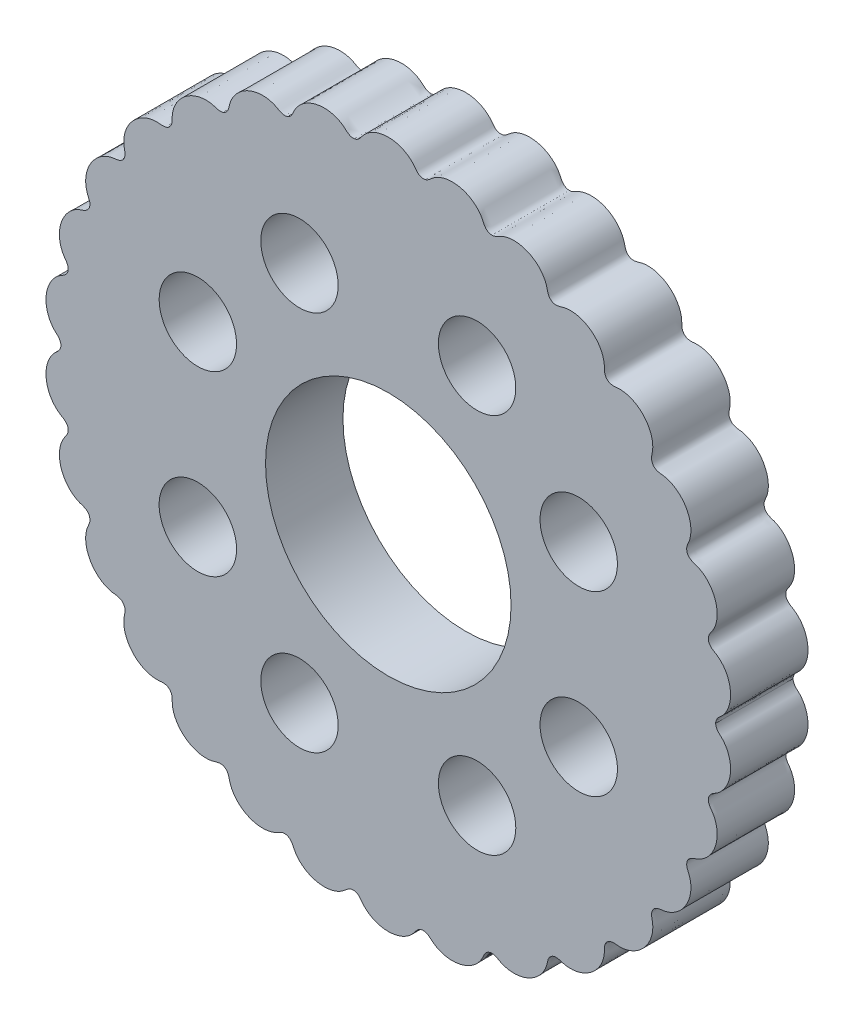
SolidWorks part; units mm, degrees
ref_plane "Plan de face" through (0, 0, 0) normal (0, 0, 1) x (1, 0, 0)
ref_plane "Plan de dessus" through (0, 0, 0) normal (0, 1, 0) x (1, 0, 0)
ref_plane "Plan de droite" through (0, 0, 0) normal (1, 0, 0) x (0, 0, -1)
sketch "Esquisse1" plane through (0, 0, 0) normal (0, 0, 1) x (1, 0, 0)
  line L0 (-1000, 0) -> (49000, 0) construction
  spline S0 degree 4 poles (29.8631, 8.2305) (29.8499, 8.1217) (29.8133, 7.9053) (29.7416, 7.64) (29.6157, 7.3353) (29.4839, 7.095) (29.3642, 6.911) (29.2467, 6.7537) (29.1538, 6.6056) (29.0902, 6.432) (29.0737, 6.2397) (29.1354, 6.023) (29.2904, 5.838) (29.4774, 5.7198) (29.6579, 5.6163) (29.8231, 5.5082) (30.0196, 5.3594) (30.2372, 5.1583) (30.5232, 4.8242) (30.8216, 4.3213) (31.0469, 3.679) (31.1337, 2.9091) (31.0567, 2.2277) (30.8902, 1.7108) (30.7109, 1.353) (30.5728, 1.1334) (30.4496, 0.9663) (30.3139, 0.8094) (30.1671, 0.6626) (30.0393, 0.549) (29.9425, 0.4546) (29.8803, 0.3777) (29.8449, 0.3262) (29.8141, 0.2716) (29.7888, 0.2141) (29.7717, 0.1632) (29.761, 0.1169) (29.7536, 0.0672) (29.7495, 0.017) (29.7494, -0.0206) (29.7556, -0.0898) (29.7678, -0.1499) (29.7904, -0.2203) (29.8284, -0.303) (29.8828, -0.3847) (29.9529, -0.4642) (30.04, -0.5488) (30.1416, -0.6407) (30.2572, -0.7512) (30.3813, -0.8854) (30.4962, -1.0277) (30.6276, -1.2147) (30.7721, -1.4641) (30.9126, -1.7829) (31.0276, -2.1744) (31.0935, -2.591) (31.107, -3.0187) (31.0662, -3.4508) (30.9693, -3.8803) (30.8145, -4.2991) (30.6117, -4.6792) (30.3965, -4.9766) (30.1917, -5.1998) (30.0146, -5.3603) (29.8643, -5.4786) (29.7061, -5.5858) (29.542, -5.684) (29.3671, -5.785) (29.2042, -5.9269) (29.0936, -6.1295) (29.0703, -6.371) (29.1391, -6.5914) (29.2598, -6.7697) (29.3791, -6.934) (29.4834, -7.0955) (29.5997, -7.3056) (29.715, -7.5703) (29.8147, -7.8969) (29.8798, -8.2857) (29.896, -8.684) (29.8631, -9.0858) (29.7829, -9.4799) (29.6574, -9.8612) (29.4885, -10.2243) (29.2783, -10.5643) (29.0303, -10.8742) (28.7824, -11.1148) (28.5506, -11.2952) (28.3468, -11.4258) (28.1768, -11.5188) (28.0006, -11.599) (27.8193, -11.6676) (27.6244, -11.7296) (27.4217, -11.8089) (27.242, -11.9571) (27.1301, -12.1734) (27.113, -12.404) (27.1707, -12.6114) (27.2542, -12.795) (27.3276, -12.9715) (27.3906, -13.1518) (27.4404, -13.3363) (27.4866, -13.5706) (27.5177, -13.8717) (27.5133, -14.2384) (27.4499, -14.6642) (27.3252, -15.0926) (27.1465, -15.4978) (26.919, -15.8739) (26.6474, -16.2153) (26.3365, -16.5168) (26.0024, -16.764) (25.654, -16.9563) (25.3418, -17.0779) (25.0791, -17.148) (24.8562, -17.1866) (24.6765, -17.2082) (24.4854, -17.2287) (24.2872, -17.2853) (24.1038, -17.4139) (23.9758, -17.6159) (23.9376, -17.8434) (23.9703, -18.0586) (24.0141, -18.2584) (24.0453, -18.4498) (24.0639, -18.6424) (24.0684, -18.8361) (24.0572, -19.0779) (24.0169, -19.3689) (23.9324, -19.7039) (23.7881, -20.0736) (23.5988, -20.4256) (23.3687, -20.7534) (23.1013, -21.0528) (22.8001, -21.3193) (22.4685, -21.5487) (22.1155, -21.7338) (21.7463, -21.8718) (21.4135, -21.9488) (21.1267, -21.9813) (20.8866, -21.9856) (20.6945, -21.9761) (20.4927, -21.9549) (20.2778, -21.9395) (20.0526, -21.9901) (19.8551, -22.131) (19.7349, -22.3281) (19.6935, -22.5401) (19.6935, -22.7421) (19.6905, -22.9333) (19.6768, -23.124) (19.6495, -23.3133) (19.599, -23.5469) (19.5081, -23.8358) (19.3582, -24.1709) (19.1304, -24.5365) (18.8451, -24.88) (18.5216, -25.1787) (18.1677, -25.4301) (17.7906, -25.6322) (17.3968, -25.7835) (17.0003, -25.8796) (16.6085, -25.9224) (16.2742, -25.9148) (16.002, -25.8785) (15.7793, -25.8278) (15.6036, -25.7769) (15.4169, -25.7147) (15.2087, -25.6689) (14.9779, -25.6954) (14.7639, -25.8189) (14.6256, -26.0056) (14.5611, -26.2088) (14.5217, -26.4015) (14.4779, -26.5791) (14.4104, -26.7974) (14.3058, -27.0513) (14.1452, -27.3445) (13.9122, -27.6625) (13.6308, -27.9579) (13.3029, -28.2232) (12.9393, -28.4488) (12.5446, -28.6295) (12.1242, -28.7604) (11.6841, -28.8357) (11.2535, -28.8501) (10.8884, -28.8124) (10.5927, -28.7466) (10.3651, -28.6736) (10.1875, -28.6026) (10.0156, -28.5191) (9.8485, -28.4261) (9.6736, -28.3252) (9.4693, -28.255) (9.2385, -28.2605) (9.0177, -28.3611) (8.8612, -28.5309) (8.7671, -28.7246) (8.6846, -28.91) (8.5968, -29.0812) (8.473, -29.2869) (8.3014, -29.519) (8.0684, -29.7687) (7.7643, -30.0195) (7.4274, -30.2327) (7.0631, -30.4051) (6.6816, -30.5327) (6.2887, -30.6146) (5.8897, -30.6499) (5.4902, -30.6379) (5.0979, -30.5781) (4.7655, -30.4837) (4.4934, -30.3731) (4.2784, -30.2619) (4.1128, -30.1612) (3.9553, -30.0487) (3.8052, -29.926) (3.6541, -29.7882) (3.484, -29.6523) (3.2679, -29.5716) (3.029, -29.5815) (2.8259, -29.676) (2.6778, -29.8193) (2.5645, -29.9746) (2.456, -30.1194) (2.311, -30.2931) (2.119, -30.4856) (1.8576, -30.6952) (1.5168, -30.9007) (1.1357, -31.0665) (0.7192, -31.185) (0.2877, -31.2495) (-0.1517, -31.2585) (-0.592, -31.2106) (-1.0254, -31.1045) (-1.4258, -30.9464) (-1.7456, -30.7669) (-1.9908, -30.5894) (-2.1706, -30.4322) (-2.3055, -30.2968) (-2.4301, -30.1521) (-2.5463, -30.0003) (-2.6635, -29.8363) (-2.8143, -29.6826) (-3.0226, -29.582) (-3.2659, -29.5708) (-3.484, -29.6523) (-3.654, -29.7882) (-3.8052, -29.926) (-3.9553, -30.0487) (-4.1128, -30.1612) (-4.2784, -30.2619) (-4.4934, -30.3731) (-4.7655, -30.4837) (-5.0979, -30.5781) (-5.4902, -30.6379) (-5.8897, -30.6499) (-6.2887, -30.6146) (-6.6816, -30.5327) (-7.0631, -30.4051) (-7.4274, -30.2327) (-7.7643, -30.0195) (-8.0684, -29.7687) (-8.3014, -29.519) (-8.473, -29.2869) (-8.5968, -29.0812) (-8.6846, -28.91) (-8.7671, -28.7246) (-8.8612, -28.5309) (-9.0177, -28.3611) (-9.2385, -28.2605) (-9.4693, -28.255) (-9.6736, -28.3252) (-9.8485, -28.4261) (-10.0156, -28.5191) (-10.1875, -28.6026) (-10.3651, -28.6736) (-10.5927, -28.7466) (-10.8884, -28.8124) (-11.2535, -28.8501) (-11.6841, -28.8357) (-12.1242, -28.7604) (-12.5446, -28.6295) (-12.9393, -28.4488) (-13.3029, -28.2232) (-13.6308, -27.9579) (-13.9122, -27.6625) (-14.1452, -27.3445) (-14.3058, -27.0513) (-14.4104, -26.7974) (-14.4779, -26.5791) (-14.5217, -26.4015) (-14.5611, -26.2088) (-14.6256, -26.0056) (-14.7639, -25.8189) (-14.9779, -25.6954) (-15.2087, -25.6689) (-15.4169, -25.7147) (-15.6036, -25.7769) (-15.7793, -25.8278) (-16.002, -25.8785) (-16.2742, -25.9148) (-16.6085, -25.9224) (-17.0003, -25.8796) (-17.3968, -25.7835) (-17.7906, -25.6322) (-18.1677, -25.4301) (-18.5216, -25.1787) (-18.8451, -24.88) (-19.1304, -24.5365) (-19.3582, -24.1709) (-19.5081, -23.8358) (-19.599, -23.5469) (-19.6495, -23.3133) (-19.6768, -23.124) (-19.6905, -22.9333) (-19.6935, -22.7421) (-19.6935, -22.5401) (-19.7349, -22.3281) (-19.8551, -22.131) (-20.0526, -21.9901) (-20.2778, -21.9395) (-20.4927, -21.9549) (-20.6945, -21.9761) (-20.8866, -21.9856) (-21.1267, -21.9813) (-21.4135, -21.9488) (-21.7463, -21.8718) (-22.1155, -21.7338) (-22.4685, -21.5487) (-22.8001, -21.3193) (-23.1013, -21.0528) (-23.3687, -20.7534) (-23.5988, -20.4256) (-23.7881, -20.0736) (-23.9324, -19.7039) (-24.0169, -19.3689) (-24.0572, -19.0779) (-24.0684, -18.8361) (-24.0639, -18.6424) (-24.0453, -18.4498) (-24.0141, -18.2584) (-23.9703, -18.0586) (-23.9376, -17.8434) (-23.9758, -17.6159) (-24.1038, -17.4139) (-24.2872, -17.2853) (-24.4854, -17.2287) (-24.6765, -17.2082) (-24.8562, -17.1866) (-25.0791, -17.148) (-25.3418, -17.0779) (-25.654, -16.9563) (-26.0024, -16.764) (-26.3365, -16.5168) (-26.6474, -16.2153) (-26.919, -15.8739) (-27.1465, -15.4978) (-27.3252, -15.0926) (-27.4499, -14.6642) (-27.5133, -14.2384) (-27.5177, -13.8717) (-27.4866, -13.5706) (-27.4404, -13.3363) (-27.3906, -13.1518) (-27.3276, -12.9715) (-27.2542, -12.795) (-27.1707, -12.6114) (-27.113, -12.404) (-27.1301, -12.1734) (-27.242, -11.9571) (-27.4217, -11.8089) (-27.6244, -11.7296) (-27.8193, -11.6676) (-28.0006, -11.599) (-28.1768, -11.5188) (-28.3468, -11.4258) (-28.5506, -11.2952) (-28.7824, -11.1148) (-29.0303, -10.8742) (-29.2783, -10.5643) (-29.4885, -10.2243) (-29.6574, -9.8612) (-29.7829, -9.4799) (-29.8631, -9.0858) (-29.896, -8.684) (-29.8798, -8.2857) (-29.8147, -7.8969) (-29.715, -7.5703) (-29.5997, -7.3056) (-29.4834, -7.0955) (-29.3791, -6.934) (-29.2598, -6.7697) (-29.1391, -6.5914) (-29.0703, -6.371) (-29.0936, -6.1295) (-29.2042, -5.9269) (-29.3671, -5.785) (-29.542, -5.684) (-29.7061, -5.5858) (-29.8643, -5.4786) (-30.0146, -5.3603) (-30.1917, -5.1998) (-30.3965, -4.9766) (-30.6117, -4.6792) (-30.8145, -4.2991) (-30.9693, -3.8803) (-31.0662, -3.4508) (-31.107, -3.0187) (-31.0935, -2.591) (-31.0276, -2.1744) (-30.9126, -1.7829) (-30.7537, -1.4222) (-30.58, -1.1364) (-30.4124, -0.919) (-30.2572, -0.7512) (-30.1416, -0.6407) (-30.04, -0.5488) (-29.9529, -0.4642) (-29.8828, -0.3847) (-29.8284, -0.303) (-29.7904, -0.2203) (-29.7678, -0.1499) (-29.7556, -0.0898) (-29.7494, -0.0206) (-29.7495, 0.0226) (-29.7561, 0.094) (-29.7693, 0.1557) (-29.7888, 0.2141) (-29.8141, 0.2716) (-29.8449, 0.3262) (-29.8803, 0.3778) (-29.9262, 0.4344) (-29.9834, 0.4947) (-30.0703, 0.5765) (-30.1854, 0.6811) (-30.3139, 0.8093) (-30.4835, 1.0056) (-30.6621, 1.2611) (-30.8291, 1.576) (-30.9678, 1.9517) (-31.0574, 2.3341) (-31.1011, 2.7166) (-31.1012, 3.1978) (-31.0148, 3.7704) (-30.8216, 4.3213) (-30.5232, 4.8242) (-30.2372, 5.1583) (-30.0196, 5.3594) (-29.8231, 5.5082) (-29.6579, 5.6163) (-29.4774, 5.7198) (-29.2904, 5.838) (-29.1354, 6.023) (-29.0737, 6.2397) (-29.0902, 6.432) (-29.1538, 6.6056) (-29.2467, 6.7537) (-29.3642, 6.911) (-29.4839, 7.095) (-29.6157, 7.3353) (-29.7416, 7.64) (-29.8133, 7.9053) (-29.8499, 8.1217) (-29.8631, 8.2305) knots 0 0 0 0 0 0.003392 0.006784 0.00848 0.010176 0.011872 0.013568 0.014566 0.015563 0.017559 0.01944 0.02132 0.022846 0.024371 0.025896 0.027421 0.030471 0.033522 0.039468 0.045414 0.051361 0.057307 0.060517 0.062121 0.063726 0.065331 0.066935 0.06854 0.070145 0.070628 0.071112 0.071596 0.07208 0.072564 0.073048 0.073289 0.073531 0.074015 0.07448 0.074945 0.07541 0.075875 0.076805 0.077735 0.078442 0.079149 0.080563 0.081977 0.083391 0.084805 0.086218 0.089046 0.092302 0.095557 0.098813 0.102069 0.105514 0.10896 0.112405 0.115851 0.118808 0.120287 0.121766 0.123244 0.124723 0.126202 0.12768 0.1295 0.131319 0.133154 0.134989 0.136475 0.137961 0.139448 0.140934 0.143906 0.146878 0.14999 0.153103 0.156215 0.159327 0.162414 0.1655 0.168586 0.171672 0.174668 0.176165 0.177663 0.179161 0.180659 0.182156 0.183654 0.185506 0.187357 0.189175 0.190994 0.192471 0.193949 0.195426 0.196904 0.198382 0.199859 0.202814 0.206257 0.2097 0.213143 0.216586 0.219928 0.22327 0.226613 0.229955 0.232755 0.235555 0.236955 0.238355 0.239755 0.241155 0.242909 0.244663 0.246515 0.248366 0.249864 0.251362 0.252859 0.254357 0.255855 0.257353 0.260348 0.263434 0.266521 0.269607 0.272693 0.275805 0.278918 0.28203 0.285143 0.288115 0.291087 0.292573 0.294059 0.295545 0.297031 0.298866 0.300701 0.302521 0.30434 0.305819 0.307297 0.308776 0.310255 0.311733 0.313212 0.31617 0.319615 0.323061 0.326506 0.329952 0.333207 0.336463 0.339719 0.342974 0.345802 0.34863 0.350043 0.351457 0.352871 0.354285 0.356145 0.358005 0.359865 0.361725 0.363139 0.364553 0.365967 0.367381 0.370208 0.373036 0.376292 0.379547 0.382803 0.386059 0.389504 0.39295 0.396395 0.399841 0.402798 0.404277 0.405755 0.407234 0.408713 0.410191 0.41167 0.41349 0.415309 0.417144 0.418979 0.420465 0.421951 0.423437 0.424923 0.427896 0.430868 0.43398 0.437092 0.440205 0.443317 0.446403 0.44949 0.452576 0.455662 0.458657 0.460155 0.461653 0.463151 0.464649 0.466146 0.467644 0.469495 0.471347 0.473101 0.474856 0.476256 0.477656 0.479056 0.480456 0.483256 0.486055 0.489398 0.49274 0.496082 0.499424 0.502867 0.50631 0.509753 0.513196 0.516151 0.517629 0.519106 0.520584 0.522061 0.523539 0.525016 0.526835 0.528653 0.530505 0.532356 0.533854 0.535351 0.536849 0.538347 0.539845 0.541343 0.544338 0.547424 0.55051 0.553597 0.556683 0.559795 0.562908 0.56602 0.569132 0.572104 0.575077 0.576563 0.578049 0.579535 0.581021 0.582856 0.584691 0.58651 0.58833 0.589809 0.591287 0.592766 0.594245 0.595723 0.597202 0.600159 0.603605 0.60705 0.610496 0.613941 0.617197 0.620453 0.623708 0.626964 0.629792 0.632619 0.634033 0.635447 0.636861 0.638275 0.640135 0.641995 0.643855 0.645715 0.647129 0.648543 0.649957 0.65137 0.654198 0.657026 0.660281 0.663537 0.666793 0.670048 0.673494 0.676939 0.680385 0.68383 0.686788 0.688267 0.689745 0.691224 0.692703 0.694181 0.69566 0.697479 0.699299 0.701134 0.702969 0.704455 0.705941 0.707427 0.708913 0.711885 0.714857 0.71797 0.721082 0.724195 0.727307 0.730393 0.733479 0.736566 0.739652 0.742647 0.744145 0.745643 0.747141 0.748638 0.750136 0.751634 0.753485 0.755337 0.757091 0.758845 0.760245 0.761645 0.763045 0.764445 0.767245 0.770045 0.773387 0.77673 0.780072 0.783414 0.786857 0.7903 0.793743 0.797186 0.800141 0.801618 0.803096 0.804574 0.806051 0.807529 0.809006 0.810825 0.812643 0.814494 0.816346 0.817844 0.819341 0.820839 0.822337 0.823835 0.825332 0.828328 0.831414 0.8345 0.837586 0.840673 0.843785 0.846897 0.85001 0.853122 0.856094 0.859066 0.860552 0.862039 0.863525 0.865011 0.866846 0.868681 0.8705 0.87232 0.873798 0.875277 0.876756 0.878234 0.879713 0.881192 0.884149 0.887595 0.89104 0.894486 0.897931 0.901187 0.904443 0.907698 0.910954 0.913782 0.916609 0.918023 0.919437 0.920851 0.921558 0.922265 0.923195 0.924125 0.92459 0.925055 0.92552 0.925985 0.926469 0.926952 0.927436 0.92792 0.928404 0.928888 0.929372 0.929855 0.930658 0.93146 0.933065 0.934669 0.936274 0.939483 0.942693 0.945666 0.948639 0.951612 0.954586 0.960532 0.966478 0.969529 0.972579 0.974104 0.975629 0.977154 0.97868 0.98056 0.982441 0.984437 0.985434 0.986432 0.988128 0.989824 0.99152 0.993216 0.996608 1 1 1 1 1 construction
  spline S1 degree 4 poles (29.75, 0) (29.75, -0.0128) (29.751, -0.0384) (29.7556, -0.0898) (29.7678, -0.1499) (29.7904, -0.2203) (29.8284, -0.303) (29.8828, -0.3847) (29.9529, -0.4642) (30.04, -0.5488) (30.1416, -0.6407) (30.2572, -0.7512) (30.3813, -0.8854) (30.4962, -1.0277) (30.6276, -1.2147) (30.7721, -1.4641) (30.9126, -1.7829) (31.0276, -2.1744) (31.0935, -2.591) (31.107, -3.0187) (31.0662, -3.4508) (30.9693, -3.8803) (30.8145, -4.2991) (30.6117, -4.6792) (30.3965, -4.9766) (30.1917, -5.1998) (30.0146, -5.3603) (29.8643, -5.4786) (29.7061, -5.5858) (29.542, -5.684) (29.3671, -5.785) (29.2042, -5.9269) (29.0936, -6.1295) (29.0703, -6.371) (29.1391, -6.5914) (29.2598, -6.7697) (29.3791, -6.934) (29.4834, -7.0955) (29.5997, -7.3056) (29.715, -7.5703) (29.8147, -7.8969) (29.8798, -8.2857) (29.896, -8.684) (29.8631, -9.0858) (29.7829, -9.4799) (29.6574, -9.8612) (29.4885, -10.2243) (29.2783, -10.5643) (29.0303, -10.8742) (28.7824, -11.1148) (28.5506, -11.2952) (28.3468, -11.4258) (28.1768, -11.5188) (28.0006, -11.599) (27.8193, -11.6676) (27.6244, -11.7296) (27.4217, -11.8089) (27.242, -11.9571) (27.1301, -12.1734) (27.113, -12.404) (27.1707, -12.6114) (27.2542, -12.795) (27.3276, -12.9715) (27.3906, -13.1518) (27.4404, -13.3363) (27.4866, -13.5706) (27.5177, -13.8717) (27.5133, -14.2384) (27.4499, -14.6642) (27.3252, -15.0926) (27.1465, -15.4978) (26.919, -15.8739) (26.6474, -16.2153) (26.3365, -16.5168) (26.0024, -16.764) (25.654, -16.9563) (25.3418, -17.0779) (25.0791, -17.148) (24.8562, -17.1866) (24.6765, -17.2082) (24.4854, -17.2287) (24.2872, -17.2853) (24.1038, -17.4139) (23.9758, -17.6159) (23.9376, -17.8434) (23.9703, -18.0586) (24.0141, -18.2584) (24.0453, -18.4498) (24.0639, -18.6424) (24.0684, -18.8361) (24.0572, -19.0779) (24.0169, -19.3689) (23.9324, -19.7039) (23.7881, -20.0736) (23.5988, -20.4256) (23.3687, -20.7534) (23.1013, -21.0528) (22.8001, -21.3193) (22.4685, -21.5487) (22.1155, -21.7338) (21.7463, -21.8718) (21.4135, -21.9488) (21.1267, -21.9813) (20.8866, -21.9856) (20.6945, -21.9761) (20.4927, -21.9549) (20.2778, -21.9395) (20.0526, -21.9901) (19.8551, -22.131) (19.7349, -22.3281) (19.6935, -22.5401) (19.6935, -22.7421) (19.6905, -22.9333) (19.6768, -23.124) (19.6495, -23.3133) (19.599, -23.5469) (19.5081, -23.8358) (19.3582, -24.1709) (19.1304, -24.5365) (18.8451, -24.88) (18.5216, -25.1787) (18.1677, -25.4301) (17.7906, -25.6322) (17.3968, -25.7835) (17.0003, -25.8796) (16.6085, -25.9224) (16.2742, -25.9148) (16.002, -25.8785) (15.7793, -25.8278) (15.6036, -25.7769) (15.4169, -25.7147) (15.2087, -25.6689) (14.9779, -25.6954) (14.7639, -25.8189) (14.6256, -26.0056) (14.5611, -26.2088) (14.5217, -26.4015) (14.4779, -26.5791) (14.4104, -26.7974) (14.3058, -27.0513) (14.1452, -27.3445) (13.9122, -27.6625) (13.6308, -27.9579) (13.3029, -28.2232) (12.9393, -28.4488) (12.5446, -28.6295) (12.1242, -28.7604) (11.6841, -28.8357) (11.2535, -28.8501) (10.8884, -28.8124) (10.5927, -28.7466) (10.3651, -28.6736) (10.1875, -28.6026) (10.0156, -28.5191) (9.8485, -28.4261) (9.6736, -28.3252) (9.4693, -28.255) (9.2385, -28.2605) (9.0177, -28.3611) (8.8612, -28.5309) (8.7671, -28.7246) (8.6846, -28.91) (8.5968, -29.0812) (8.473, -29.2869) (8.3014, -29.519) (8.0684, -29.7687) (7.7643, -30.0195) (7.4274, -30.2327) (7.0631, -30.4051) (6.6816, -30.5327) (6.2887, -30.6146) (5.8897, -30.6499) (5.4902, -30.6379) (5.0979, -30.5781) (4.7655, -30.4837) (4.4934, -30.3731) (4.2784, -30.2619) (4.1128, -30.1612) (3.9553, -30.0487) (3.8052, -29.926) (3.6541, -29.7882) (3.484, -29.6523) (3.2679, -29.5716) (3.029, -29.5815) (2.8259, -29.676) (2.6778, -29.8193) (2.5645, -29.9746) (2.456, -30.1194) (2.311, -30.2931) (2.119, -30.4856) (1.8576, -30.6952) (1.5168, -30.9007) (1.1357, -31.0665) (0.7192, -31.185) (0.2877, -31.2495) (-0.1517, -31.2585) (-0.592, -31.2106) (-1.0254, -31.1045) (-1.4258, -30.9464) (-1.7456, -30.7669) (-1.9908, -30.5894) (-2.1706, -30.4322) (-2.3055, -30.2968) (-2.4301, -30.1521) (-2.5463, -30.0003) (-2.6635, -29.8363) (-2.8143, -29.6826) (-3.0226, -29.582) (-3.2659, -29.5708) (-3.484, -29.6523) (-3.654, -29.7882) (-3.8052, -29.926) (-3.9553, -30.0487) (-4.1128, -30.1612) (-4.2784, -30.2619) (-4.4934, -30.3731) (-4.7655, -30.4837) (-5.0979, -30.5781) (-5.4902, -30.6379) (-5.8897, -30.6499) (-6.2887, -30.6146) (-6.6816, -30.5327) (-7.0631, -30.4051) (-7.4274, -30.2327) (-7.7643, -30.0195) (-8.0684, -29.7687) (-8.3014, -29.519) (-8.473, -29.2869) (-8.5968, -29.0812) (-8.6846, -28.91) (-8.7671, -28.7246) (-8.8612, -28.5309) (-9.0177, -28.3611) (-9.2385, -28.2605) (-9.4693, -28.255) (-9.6736, -28.3252) (-9.8485, -28.4261) (-10.0156, -28.5191) (-10.1875, -28.6026) (-10.3651, -28.6736) (-10.5927, -28.7466) (-10.8884, -28.8124) (-11.2535, -28.8501) (-11.6841, -28.8357) (-12.1242, -28.7604) (-12.5446, -28.6295) (-12.9393, -28.4488) (-13.3029, -28.2232) (-13.6308, -27.9579) (-13.9122, -27.6625) (-14.1452, -27.3445) (-14.3058, -27.0513) (-14.4104, -26.7974) (-14.4779, -26.5791) (-14.5217, -26.4015) (-14.5611, -26.2088) (-14.6256, -26.0056) (-14.7639, -25.8189) (-14.9779, -25.6954) (-15.2087, -25.6689) (-15.4169, -25.7147) (-15.6036, -25.7769) (-15.7793, -25.8278) (-16.002, -25.8785) (-16.2742, -25.9148) (-16.6085, -25.9224) (-17.0003, -25.8796) (-17.3968, -25.7835) (-17.7906, -25.6322) (-18.1677, -25.4301) (-18.5216, -25.1787) (-18.8451, -24.88) (-19.1304, -24.5365) (-19.3582, -24.1709) (-19.5081, -23.8358) (-19.599, -23.5469) (-19.6495, -23.3133) (-19.6768, -23.124) (-19.6905, -22.9333) (-19.6935, -22.7421) (-19.6935, -22.5401) (-19.7349, -22.3281) (-19.8551, -22.131) (-20.0526, -21.9901) (-20.2778, -21.9395) (-20.4927, -21.9549) (-20.6945, -21.9761) (-20.8866, -21.9856) (-21.1267, -21.9813) (-21.4135, -21.9488) (-21.7463, -21.8718) (-22.1155, -21.7338) (-22.4685, -21.5487) (-22.8001, -21.3193) (-23.1013, -21.0528) (-23.3687, -20.7534) (-23.5988, -20.4256) (-23.7881, -20.0736) (-23.9324, -19.7039) (-24.0169, -19.3689) (-24.0572, -19.0779) (-24.0684, -18.8361) (-24.0639, -18.6424) (-24.0453, -18.4498) (-24.0141, -18.2584) (-23.9703, -18.0586) (-23.9376, -17.8434) (-23.9758, -17.6159) (-24.1038, -17.4139) (-24.2872, -17.2853) (-24.4854, -17.2287) (-24.6765, -17.2082) (-24.8562, -17.1866) (-25.0791, -17.148) (-25.3418, -17.0779) (-25.654, -16.9563) (-26.0024, -16.764) (-26.3365, -16.5168) (-26.6474, -16.2153) (-26.919, -15.8739) (-27.1465, -15.4978) (-27.3252, -15.0926) (-27.4499, -14.6642) (-27.5133, -14.2384) (-27.5177, -13.8717) (-27.4866, -13.5706) (-27.4404, -13.3363) (-27.3906, -13.1518) (-27.3276, -12.9715) (-27.2542, -12.795) (-27.1707, -12.6114) (-27.113, -12.404) (-27.1301, -12.1734) (-27.242, -11.9571) (-27.4217, -11.8089) (-27.6244, -11.7296) (-27.8193, -11.6676) (-28.0006, -11.599) (-28.1768, -11.5188) (-28.3468, -11.4258) (-28.5506, -11.2952) (-28.7824, -11.1148) (-29.0303, -10.8742) (-29.2783, -10.5643) (-29.4885, -10.2243) (-29.6574, -9.8612) (-29.7829, -9.4799) (-29.8631, -9.0858) (-29.896, -8.684) (-29.8798, -8.2857) (-29.8147, -7.8969) (-29.715, -7.5703) (-29.5997, -7.3056) (-29.4834, -7.0955) (-29.3791, -6.934) (-29.2598, -6.7697) (-29.1391, -6.5914) (-29.0703, -6.371) (-29.0936, -6.1295) (-29.2042, -5.9269) (-29.3671, -5.785) (-29.542, -5.684) (-29.7061, -5.5858) (-29.8643, -5.4786) (-30.0146, -5.3603) (-30.1917, -5.1998) (-30.3965, -4.9766) (-30.6117, -4.6792) (-30.8145, -4.2991) (-30.9693, -3.8803) (-31.0662, -3.4508) (-31.107, -3.0187) (-31.0935, -2.591) (-31.0276, -2.1744) (-30.9126, -1.7829) (-30.7537, -1.4222) (-30.58, -1.1364) (-30.4124, -0.919) (-30.2572, -0.7512) (-30.1416, -0.6407) (-30.04, -0.5488) (-29.9529, -0.4642) (-29.8828, -0.3847) (-29.8284, -0.303) (-29.7904, -0.2203) (-29.7678, -0.1499) (-29.7556, -0.0898) (-29.751, -0.0384) (-29.75, -0.0128) (-29.75, 0) knots 0.074015 0.074015 0.074015 0.074015 0.074015 0.07448 0.074945 0.07541 0.075875 0.076805 0.077735 0.078442 0.079149 0.080563 0.081977 0.083391 0.084805 0.086218 0.089046 0.092302 0.095557 0.098813 0.102069 0.105514 0.10896 0.112405 0.115851 0.118808 0.120287 0.121766 0.123244 0.124723 0.126202 0.12768 0.1295 0.131319 0.133154 0.134989 0.136475 0.137961 0.139448 0.140934 0.143906 0.146878 0.14999 0.153103 0.156215 0.159327 0.162414 0.1655 0.168586 0.171672 0.174668 0.176165 0.177663 0.179161 0.180659 0.182156 0.183654 0.185506 0.187357 0.189175 0.190994 0.192471 0.193949 0.195426 0.196904 0.198382 0.199859 0.202814 0.206257 0.2097 0.213143 0.216586 0.219928 0.22327 0.226613 0.229955 0.232755 0.235555 0.236955 0.238355 0.239755 0.241155 0.242909 0.244663 0.246515 0.248366 0.249864 0.251362 0.252859 0.254357 0.255855 0.257353 0.260348 0.263434 0.266521 0.269607 0.272693 0.275805 0.278918 0.28203 0.285143 0.288115 0.291087 0.292573 0.294059 0.295545 0.297031 0.298866 0.300701 0.302521 0.30434 0.305819 0.307297 0.308776 0.310255 0.311733 0.313212 0.31617 0.319615 0.323061 0.326506 0.329952 0.333207 0.336463 0.339719 0.342974 0.345802 0.34863 0.350043 0.351457 0.352871 0.354285 0.356145 0.358005 0.359865 0.361725 0.363139 0.364553 0.365967 0.367381 0.370208 0.373036 0.376292 0.379547 0.382803 0.386059 0.389504 0.39295 0.396395 0.399841 0.402798 0.404277 0.405755 0.407234 0.408713 0.410191 0.41167 0.41349 0.415309 0.417144 0.418979 0.420465 0.421951 0.423437 0.424923 0.427896 0.430868 0.43398 0.437092 0.440205 0.443317 0.446403 0.44949 0.452576 0.455662 0.458657 0.460155 0.461653 0.463151 0.464649 0.466146 0.467644 0.469495 0.471347 0.473101 0.474856 0.476256 0.477656 0.479056 0.480456 0.483256 0.486055 0.489398 0.49274 0.496082 0.499424 0.502867 0.50631 0.509753 0.513196 0.516151 0.517629 0.519106 0.520584 0.522061 0.523539 0.525016 0.526835 0.528653 0.530505 0.532356 0.533854 0.535351 0.536849 0.538347 0.539845 0.541343 0.544338 0.547424 0.55051 0.553597 0.556683 0.559795 0.562908 0.56602 0.569132 0.572104 0.575077 0.576563 0.578049 0.579535 0.581021 0.582856 0.584691 0.58651 0.58833 0.589809 0.591287 0.592766 0.594245 0.595723 0.597202 0.600159 0.603605 0.60705 0.610496 0.613941 0.617197 0.620453 0.623708 0.626964 0.629792 0.632619 0.634033 0.635447 0.636861 0.638275 0.640135 0.641995 0.643855 0.645715 0.647129 0.648543 0.649957 0.65137 0.654198 0.657026 0.660281 0.663537 0.666793 0.670048 0.673494 0.676939 0.680385 0.68383 0.686788 0.688267 0.689745 0.691224 0.692703 0.694181 0.69566 0.697479 0.699299 0.701134 0.702969 0.704455 0.705941 0.707427 0.708913 0.711885 0.714857 0.71797 0.721082 0.724195 0.727307 0.730393 0.733479 0.736566 0.739652 0.742647 0.744145 0.745643 0.747141 0.748638 0.750136 0.751634 0.753485 0.755337 0.757091 0.758845 0.760245 0.761645 0.763045 0.764445 0.767245 0.770045 0.773387 0.77673 0.780072 0.783414 0.786857 0.7903 0.793743 0.797186 0.800141 0.801618 0.803096 0.804574 0.806051 0.807529 0.809006 0.810825 0.812643 0.814494 0.816346 0.817844 0.819341 0.820839 0.822337 0.823835 0.825332 0.828328 0.831414 0.8345 0.837586 0.840673 0.843785 0.846897 0.85001 0.853122 0.856094 0.859066 0.860552 0.862039 0.863525 0.865011 0.866846 0.868681 0.8705 0.87232 0.873798 0.875277 0.876756 0.878234 0.879713 0.881192 0.884149 0.887595 0.89104 0.894486 0.897931 0.901187 0.904443 0.907698 0.910954 0.913782 0.916609 0.918023 0.919437 0.920851 0.921558 0.922265 0.923195 0.924125 0.92459 0.925055 0.92552 0.925985 0.925985 0.925985 0.925985 0.925985 construction
  spline S2 degree 4 poles (29.75, 0) (29.75, 0.0128) (29.751, 0.0384) (29.7556, 0.0898) (29.7678, 0.1499) (29.7904, 0.2203) (29.8284, 0.303) (29.8828, 0.3847) (29.9529, 0.4642) (30.04, 0.5488) (30.1416, 0.6407) (30.2572, 0.7512) (30.3813, 0.8854) (30.4962, 1.0277) (30.6276, 1.2147) (30.7721, 1.4641) (30.9126, 1.7829) (31.0276, 2.1744) (31.0935, 2.591) (31.107, 3.0187) (31.0662, 3.4508) (30.9693, 3.8803) (30.8145, 4.2991) (30.6117, 4.6792) (30.3965, 4.9766) (30.1917, 5.1998) (30.0146, 5.3603) (29.8643, 5.4786) (29.7061, 5.5858) (29.542, 5.684) (29.3671, 5.785) (29.2042, 5.9269) (29.0936, 6.1295) (29.0703, 6.371) (29.1391, 6.5914) (29.2598, 6.7697) (29.3791, 6.934) (29.4834, 7.0955) (29.5997, 7.3056) (29.715, 7.5703) (29.8147, 7.8969) (29.8798, 8.2857) (29.896, 8.684) (29.8631, 9.0858) (29.7829, 9.4799) (29.6574, 9.8612) (29.4885, 10.2243) (29.2783, 10.5643) (29.0303, 10.8742) (28.7824, 11.1148) (28.5506, 11.2952) (28.3468, 11.4258) (28.1768, 11.5188) (28.0006, 11.599) (27.8193, 11.6676) (27.6244, 11.7296) (27.4217, 11.8089) (27.242, 11.9571) (27.1301, 12.1734) (27.113, 12.404) (27.1707, 12.6114) (27.2542, 12.795) (27.3276, 12.9715) (27.3906, 13.1518) (27.4404, 13.3363) (27.4866, 13.5706) (27.5177, 13.8717) (27.5133, 14.2384) (27.4499, 14.6642) (27.3252, 15.0926) (27.1465, 15.4978) (26.919, 15.8739) (26.6474, 16.2153) (26.3365, 16.5168) (26.0024, 16.764) (25.654, 16.9563) (25.3418, 17.0779) (25.0791, 17.148) (24.8562, 17.1866) (24.6765, 17.2082) (24.4854, 17.2287) (24.2872, 17.2853) (24.1038, 17.4139) (23.9758, 17.6159) (23.9376, 17.8434) (23.9703, 18.0586) (24.0141, 18.2584) (24.0453, 18.4498) (24.0639, 18.6424) (24.0684, 18.8361) (24.0572, 19.0779) (24.0169, 19.3689) (23.9324, 19.7039) (23.7881, 20.0736) (23.5988, 20.4256) (23.3687, 20.7534) (23.1013, 21.0528) (22.8001, 21.3193) (22.4685, 21.5487) (22.1155, 21.7338) (21.7463, 21.8718) (21.4135, 21.9488) (21.1267, 21.9813) (20.8866, 21.9856) (20.6945, 21.9761) (20.4927, 21.9549) (20.2778, 21.9395) (20.0526, 21.9901) (19.8551, 22.131) (19.7349, 22.3281) (19.6935, 22.5401) (19.6935, 22.7421) (19.6905, 22.9333) (19.6768, 23.124) (19.6495, 23.3133) (19.599, 23.5469) (19.5081, 23.8358) (19.3582, 24.1709) (19.1304, 24.5365) (18.8451, 24.88) (18.5216, 25.1787) (18.1677, 25.4301) (17.7906, 25.6322) (17.3968, 25.7835) (17.0003, 25.8796) (16.6085, 25.9224) (16.2742, 25.9148) (16.002, 25.8785) (15.7793, 25.8278) (15.6036, 25.7769) (15.4169, 25.7147) (15.2087, 25.6689) (14.9779, 25.6954) (14.7639, 25.8189) (14.6256, 26.0056) (14.5611, 26.2088) (14.5217, 26.4015) (14.4779, 26.5791) (14.4104, 26.7974) (14.3058, 27.0513) (14.1452, 27.3445) (13.9122, 27.6625) (13.6308, 27.9579) (13.3029, 28.2232) (12.9393, 28.4488) (12.5446, 28.6295) (12.1242, 28.7604) (11.6841, 28.8357) (11.2535, 28.8501) (10.8884, 28.8124) (10.5927, 28.7466) (10.3651, 28.6736) (10.1875, 28.6026) (10.0156, 28.5191) (9.8485, 28.4261) (9.6736, 28.3252) (9.4693, 28.255) (9.2385, 28.2605) (9.0177, 28.3611) (8.8612, 28.5309) (8.7671, 28.7246) (8.6846, 28.91) (8.5968, 29.0812) (8.473, 29.2869) (8.3014, 29.519) (8.0684, 29.7687) (7.7643, 30.0195) (7.4274, 30.2327) (7.0631, 30.4051) (6.6816, 30.5327) (6.2887, 30.6146) (5.8897, 30.6499) (5.4902, 30.6379) (5.0979, 30.5781) (4.7655, 30.4837) (4.4934, 30.3731) (4.2784, 30.2619) (4.1128, 30.1612) (3.9553, 30.0487) (3.8052, 29.926) (3.6541, 29.7882) (3.484, 29.6523) (3.2679, 29.5716) (3.029, 29.5815) (2.8259, 29.676) (2.6778, 29.8193) (2.5645, 29.9746) (2.456, 30.1194) (2.311, 30.2931) (2.119, 30.4856) (1.8576, 30.6952) (1.5168, 30.9007) (1.1357, 31.0665) (0.7192, 31.185) (0.2877, 31.2495) (-0.1517, 31.2585) (-0.592, 31.2106) (-1.0254, 31.1045) (-1.4258, 30.9464) (-1.7456, 30.7669) (-1.9908, 30.5894) (-2.1706, 30.4322) (-2.3055, 30.2968) (-2.4301, 30.1521) (-2.5463, 30.0003) (-2.6635, 29.8363) (-2.8143, 29.6826) (-3.0226, 29.582) (-3.2659, 29.5708) (-3.484, 29.6523) (-3.654, 29.7882) (-3.8052, 29.926) (-3.9553, 30.0487) (-4.1128, 30.1612) (-4.2784, 30.2619) (-4.4934, 30.3731) (-4.7655, 30.4837) (-5.0979, 30.5781) (-5.4902, 30.6379) (-5.8897, 30.6499) (-6.2887, 30.6146) (-6.6816, 30.5327) (-7.0631, 30.4051) (-7.4274, 30.2327) (-7.7643, 30.0195) (-8.0684, 29.7687) (-8.3014, 29.519) (-8.473, 29.2869) (-8.5968, 29.0812) (-8.6846, 28.91) (-8.7671, 28.7246) (-8.8612, 28.5309) (-9.0177, 28.3611) (-9.2385, 28.2605) (-9.4693, 28.255) (-9.6736, 28.3252) (-9.8485, 28.4261) (-10.0156, 28.5191) (-10.1875, 28.6026) (-10.3651, 28.6736) (-10.5927, 28.7466) (-10.8884, 28.8124) (-11.2535, 28.8501) (-11.6841, 28.8357) (-12.1242, 28.7604) (-12.5446, 28.6295) (-12.9393, 28.4488) (-13.3029, 28.2232) (-13.6308, 27.9579) (-13.9122, 27.6625) (-14.1452, 27.3445) (-14.3058, 27.0513) (-14.4104, 26.7974) (-14.4779, 26.5791) (-14.5217, 26.4015) (-14.5611, 26.2088) (-14.6256, 26.0056) (-14.7639, 25.8189) (-14.9779, 25.6954) (-15.2087, 25.6689) (-15.4169, 25.7147) (-15.6036, 25.7769) (-15.7793, 25.8278) (-16.002, 25.8785) (-16.2742, 25.9148) (-16.6085, 25.9224) (-17.0003, 25.8796) (-17.3968, 25.7835) (-17.7906, 25.6322) (-18.1677, 25.4301) (-18.5216, 25.1787) (-18.8451, 24.88) (-19.1304, 24.5365) (-19.3582, 24.1709) (-19.5081, 23.8358) (-19.599, 23.5469) (-19.6495, 23.3133) (-19.6768, 23.124) (-19.6905, 22.9333) (-19.6935, 22.7421) (-19.6935, 22.5401) (-19.7349, 22.3281) (-19.8551, 22.131) (-20.0526, 21.9901) (-20.2778, 21.9395) (-20.4927, 21.9549) (-20.6945, 21.9761) (-20.8866, 21.9856) (-21.1267, 21.9813) (-21.4135, 21.9488) (-21.7463, 21.8718) (-22.1155, 21.7338) (-22.4685, 21.5487) (-22.8001, 21.3193) (-23.1013, 21.0528) (-23.3687, 20.7534) (-23.5988, 20.4256) (-23.7881, 20.0736) (-23.9324, 19.7039) (-24.0169, 19.3689) (-24.0572, 19.0779) (-24.0684, 18.8361) (-24.0639, 18.6424) (-24.0453, 18.4498) (-24.0141, 18.2584) (-23.9703, 18.0586) (-23.9376, 17.8434) (-23.9758, 17.6159) (-24.1038, 17.4139) (-24.2872, 17.2853) (-24.4854, 17.2287) (-24.6765, 17.2082) (-24.8562, 17.1866) (-25.0791, 17.148) (-25.3418, 17.0779) (-25.654, 16.9563) (-26.0024, 16.764) (-26.3365, 16.5168) (-26.6474, 16.2153) (-26.919, 15.8739) (-27.1465, 15.4978) (-27.3252, 15.0926) (-27.4499, 14.6642) (-27.5133, 14.2384) (-27.5177, 13.8717) (-27.4866, 13.5706) (-27.4404, 13.3363) (-27.3906, 13.1518) (-27.3276, 12.9715) (-27.2542, 12.795) (-27.1707, 12.6114) (-27.113, 12.404) (-27.1301, 12.1734) (-27.242, 11.9571) (-27.4217, 11.8089) (-27.6244, 11.7296) (-27.8193, 11.6676) (-28.0006, 11.599) (-28.1768, 11.5188) (-28.3468, 11.4258) (-28.5506, 11.2952) (-28.7824, 11.1148) (-29.0303, 10.8742) (-29.2783, 10.5643) (-29.4885, 10.2243) (-29.6574, 9.8612) (-29.7829, 9.4799) (-29.8631, 9.0858) (-29.896, 8.684) (-29.8798, 8.2857) (-29.8147, 7.8969) (-29.715, 7.5703) (-29.5997, 7.3056) (-29.4834, 7.0955) (-29.3791, 6.934) (-29.2598, 6.7697) (-29.1391, 6.5914) (-29.0703, 6.371) (-29.0936, 6.1295) (-29.2042, 5.9269) (-29.3671, 5.785) (-29.542, 5.684) (-29.7061, 5.5858) (-29.8643, 5.4786) (-30.0146, 5.3603) (-30.1917, 5.1998) (-30.3965, 4.9766) (-30.6117, 4.6792) (-30.8145, 4.2991) (-30.9693, 3.8803) (-31.0662, 3.4508) (-31.107, 3.0187) (-31.0935, 2.591) (-31.0276, 2.1744) (-30.9126, 1.7829) (-30.7537, 1.4222) (-30.58, 1.1364) (-30.4124, 0.919) (-30.2572, 0.7512) (-30.1416, 0.6407) (-30.04, 0.5488) (-29.9529, 0.4642) (-29.8828, 0.3847) (-29.8284, 0.303) (-29.7904, 0.2203) (-29.7678, 0.1499) (-29.7556, 0.0898) (-29.751, 0.0384) (-29.75, 0.0128) (-29.75, 0) knots 0.074015 0.074015 0.074015 0.074015 0.074015 0.07448 0.074945 0.07541 0.075875 0.076805 0.077735 0.078442 0.079149 0.080563 0.081977 0.083391 0.084805 0.086218 0.089046 0.092302 0.095557 0.098813 0.102069 0.105514 0.10896 0.112405 0.115851 0.118808 0.120287 0.121766 0.123244 0.124723 0.126202 0.12768 0.1295 0.131319 0.133154 0.134989 0.136475 0.137961 0.139448 0.140934 0.143906 0.146878 0.14999 0.153103 0.156215 0.159327 0.162414 0.1655 0.168586 0.171672 0.174668 0.176165 0.177663 0.179161 0.180659 0.182156 0.183654 0.185506 0.187357 0.189175 0.190994 0.192471 0.193949 0.195426 0.196904 0.198382 0.199859 0.202814 0.206257 0.2097 0.213143 0.216586 0.219928 0.22327 0.226613 0.229955 0.232755 0.235555 0.236955 0.238355 0.239755 0.241155 0.242909 0.244663 0.246515 0.248366 0.249864 0.251362 0.252859 0.254357 0.255855 0.257353 0.260348 0.263434 0.266521 0.269607 0.272693 0.275805 0.278918 0.28203 0.285143 0.288115 0.291087 0.292573 0.294059 0.295545 0.297031 0.298866 0.300701 0.302521 0.30434 0.305819 0.307297 0.308776 0.310255 0.311733 0.313212 0.31617 0.319615 0.323061 0.326506 0.329952 0.333207 0.336463 0.339719 0.342974 0.345802 0.34863 0.350043 0.351457 0.352871 0.354285 0.356145 0.358005 0.359865 0.361725 0.363139 0.364553 0.365967 0.367381 0.370208 0.373036 0.376292 0.379547 0.382803 0.386059 0.389504 0.39295 0.396395 0.399841 0.402798 0.404277 0.405755 0.407234 0.408713 0.410191 0.41167 0.41349 0.415309 0.417144 0.418979 0.420465 0.421951 0.423437 0.424923 0.427896 0.430868 0.43398 0.437092 0.440205 0.443317 0.446403 0.44949 0.452576 0.455662 0.458657 0.460155 0.461653 0.463151 0.464649 0.466146 0.467644 0.469495 0.471347 0.473101 0.474856 0.476256 0.477656 0.479056 0.480456 0.483256 0.486055 0.489398 0.49274 0.496082 0.499424 0.502867 0.50631 0.509753 0.513196 0.516151 0.517629 0.519106 0.520584 0.522061 0.523539 0.525016 0.526835 0.528653 0.530505 0.532356 0.533854 0.535351 0.536849 0.538347 0.539845 0.541343 0.544338 0.547424 0.55051 0.553597 0.556683 0.559795 0.562908 0.56602 0.569132 0.572104 0.575077 0.576563 0.578049 0.579535 0.581021 0.582856 0.584691 0.58651 0.58833 0.589809 0.591287 0.592766 0.594245 0.595723 0.597202 0.600159 0.603605 0.60705 0.610496 0.613941 0.617197 0.620453 0.623708 0.626964 0.629792 0.632619 0.634033 0.635447 0.636861 0.638275 0.640135 0.641995 0.643855 0.645715 0.647129 0.648543 0.649957 0.65137 0.654198 0.657026 0.660281 0.663537 0.666793 0.670048 0.673494 0.676939 0.680385 0.68383 0.686788 0.688267 0.689745 0.691224 0.692703 0.694181 0.69566 0.697479 0.699299 0.701134 0.702969 0.704455 0.705941 0.707427 0.708913 0.711885 0.714857 0.71797 0.721082 0.724195 0.727307 0.730393 0.733479 0.736566 0.739652 0.742647 0.744145 0.745643 0.747141 0.748638 0.750136 0.751634 0.753485 0.755337 0.757091 0.758845 0.760245 0.761645 0.763045 0.764445 0.767245 0.770045 0.773387 0.77673 0.780072 0.783414 0.786857 0.7903 0.793743 0.797186 0.800141 0.801618 0.803096 0.804574 0.806051 0.807529 0.809006 0.810825 0.812643 0.814494 0.816346 0.817844 0.819341 0.820839 0.822337 0.823835 0.825332 0.828328 0.831414 0.8345 0.837586 0.840673 0.843785 0.846897 0.85001 0.853122 0.856094 0.859066 0.860552 0.862039 0.863525 0.865011 0.866846 0.868681 0.8705 0.87232 0.873798 0.875277 0.876756 0.878234 0.879713 0.881192 0.884149 0.887595 0.89104 0.894486 0.897931 0.901187 0.904443 0.907698 0.910954 0.913782 0.916609 0.918023 0.919437 0.920851 0.921558 0.922265 0.923195 0.924125 0.92459 0.925055 0.92552 0.925985 0.925985 0.925985 0.925985 0.925985 construction
  spline S3 degree 1 poles (29.6, 0) (-29.6, 0) knots 0 0 1 1 construction
  spline S4 degree 1 poles (29.6, 0) (-29.6, 0) knots 0 0 1 1 construction
  spline S5 degree 3 poles (29.6, 0) (29.6, -0.1735) (29.7591, -0.5357) (30.111, -0.799) (30.3738, -1.1035) (30.671, -1.5609) (30.9065, -2.2081) (30.9799, -3.0334) (30.8452, -3.8514) (30.565, -4.4818) (30.2465, -4.9257) (29.9603, -5.2176) (29.641, -5.4652) (29.2508, -5.6474) (28.8853, -6.0973) (28.9773, -6.6783) (29.2718, -7.0223) (29.4688, -7.3692) (29.6197, -7.7504) (29.7401, -8.2826) (29.7518, -8.9726) (29.5554, -9.7779) (29.1653, -10.5087) (28.6953, -11.0132) (28.2448, -11.319) (27.8806, -11.4998) (27.4716, -11.5959) (27.0063, -11.9334) (26.9433, -12.5217) (27.1609, -12.9317) (27.2862, -13.3081) (27.3824, -13.8469) (27.3471, -14.5335) (27.0918, -15.3219) (26.6477, -16.0219) (26.1434, -16.4928) (25.6766, -16.7777) (25.3004, -16.9355) (24.9061, -17.0409) (24.4941, -17.0529) (23.9642, -17.2581) (23.7482, -17.8113) (23.8719, -18.2721) (23.922, -18.6627) (23.9126, -19.0738) (23.8166, -19.6102) (23.5578, -20.2501) (23.062, -20.9141) (22.5244, -21.3478) (22.0392, -21.6023) (21.6535, -21.7422) (21.2538, -21.8226) (20.8445, -21.8474) (20.446, -21.7796) (19.888, -21.8424) (19.5332, -22.3215) (19.5491, -22.8099) (19.5236, -23.2013) (19.402, -23.7364) (19.1027, -24.3541) (18.5592, -24.98) (17.8765, -25.4502) (17.2284, -25.6867) (16.687, -25.7671) (16.2795, -25.767) (15.8725, -25.7094) (15.4994, -25.5678) (14.9519, -25.4896) (14.4825, -25.859) (14.382, -26.3502) (14.2832, -26.7277) (14.1135, -27.1035) (13.8172, -27.5599) (13.3289, -28.0479) (12.6127, -28.4649) (11.8158, -28.6913) (11.1255, -28.7036) (10.5928, -28.5963) (10.2046, -28.4583) (9.8697, -28.2506) (9.3666, -28.0415) (8.8157, -28.2748) (8.5971, -28.7385) (8.4288, -29.0903) (8.1073, -29.536) (7.5922, -29.9883) (6.8469, -30.3518) (6.0348, -30.5172) (5.3457, -30.4815) (4.8156, -30.3444) (4.44, -30.1865) (4.0869, -29.9733) (3.799, -29.7076) (3.3711, -29.3874) (2.7777, -29.4669) (2.4471, -29.8739) (2.2156, -30.1875) (1.9121, -30.4672) (1.4624, -30.7726) (0.8221, -31.031) (0, -31.1345) (-0.8221, -31.031) (-1.4623, -30.7726) (-1.9121, -30.4672) (-2.2156, -30.1875) (-2.447, -29.874) (-2.7777, -29.4669) (-3.3711, -29.3874) (-3.799, -29.7076) (-4.0869, -29.9733) (-4.44, -30.1865) (-4.8156, -30.3444) (-5.3457, -30.4815) (-6.0348, -30.5172) (-6.8469, -30.3518) (-7.5922, -29.9883) (-8.1073, -29.536) (-8.4288, -29.0903) (-8.5971, -28.7385) (-8.8157, -28.2748) (-9.3666, -28.0415) (-9.8697, -28.2506) (-10.2046, -28.4583) (-10.5928, -28.5963) (-11.1255, -28.7036) (-11.8158, -28.6913) (-12.6127, -28.4649) (-13.3289, -28.0479) (-13.8172, -27.5599) (-14.1135, -27.1035) (-14.2832, -26.7277) (-14.382, -26.3502) (-14.4825, -25.859) (-14.9519, -25.4896) (-15.4994, -25.5678) (-15.8725, -25.7094) (-16.2795, -25.767) (-16.687, -25.7671) (-17.2284, -25.6867) (-17.8765, -25.4502) (-18.5592, -24.98) (-19.1027, -24.3541) (-19.402, -23.7364) (-19.5236, -23.2013) (-19.5491, -22.8099) (-19.5332, -22.3215) (-19.888, -21.8424) (-20.446, -21.7796) (-20.8445, -21.8474) (-21.2538, -21.8226) (-21.6535, -21.7422) (-22.0392, -21.6023) (-22.5244, -21.3478) (-23.062, -20.9141) (-23.5578, -20.2501) (-23.8166, -19.6102) (-23.9126, -19.0738) (-23.922, -18.6627) (-23.8719, -18.2721) (-23.7482, -17.8113) (-23.9642, -17.2581) (-24.4941, -17.0529) (-24.9061, -17.0409) (-25.3004, -16.9355) (-25.6766, -16.7777) (-26.1434, -16.4928) (-26.6477, -16.0219) (-27.0918, -15.3219) (-27.3471, -14.5335) (-27.3824, -13.8469) (-27.2862, -13.3081) (-27.1609, -12.9317) (-26.9433, -12.5217) (-27.0063, -11.9334) (-27.4716, -11.5959) (-27.8806, -11.4998) (-28.2448, -11.319) (-28.6953, -11.0132) (-29.1653, -10.5087) (-29.5554, -9.7779) (-29.7518, -8.9726) (-29.7401, -8.2826) (-29.6197, -7.7504) (-29.4688, -7.3692) (-29.2718, -7.0223) (-28.9773, -6.6783) (-28.8853, -6.0973) (-29.2508, -5.6474) (-29.641, -5.4652) (-29.9603, -5.2176) (-30.2465, -4.9257) (-30.565, -4.4818) (-30.8452, -3.8514) (-30.9799, -3.0334) (-30.9065, -2.2081) (-30.671, -1.5609) (-30.3738, -1.1035) (-30.111, -0.799) (-29.7591, -0.5357) (-29.6, -0.1735) (-29.6, 0) knots 0.074015 0.074015 0.074015 0.074015 0.077343 0.080671 0.083999 0.087327 0.093983 0.100639 0.107295 0.113951 0.117279 0.120607 0.123935 0.127263 0.130591 0.133919 0.137247 0.140575 0.143903 0.147231 0.153887 0.160543 0.167199 0.173855 0.177183 0.180511 0.183839 0.187167 0.190495 0.193823 0.197151 0.200479 0.207135 0.213792 0.220448 0.227104 0.230432 0.23376 0.237088 0.240416 0.243744 0.247072 0.2504 0.253728 0.257056 0.260384 0.26704 0.273696 0.280352 0.28368 0.287008 0.290336 0.293664 0.296992 0.30032 0.303648 0.306976 0.310304 0.313632 0.320288 0.326944 0.3336 0.340256 0.343584 0.346912 0.35024 0.353568 0.356896 0.360224 0.363552 0.36688 0.370208 0.373536 0.380192 0.386848 0.393504 0.40016 0.403488 0.406816 0.410144 0.413472 0.4168 0.420128 0.423456 0.426784 0.43344 0.440096 0.446752 0.453408 0.456736 0.460064 0.463392 0.46672 0.470048 0.473376 0.476704 0.480032 0.48336 0.486688 0.493344 0.5 0.506656 0.513312 0.51664 0.519968 0.523296 0.526624 0.529952 0.53328 0.536608 0.539936 0.543264 0.546592 0.553248 0.559904 0.56656 0.573216 0.576544 0.579872 0.5832 0.586528 0.589856 0.593184 0.596512 0.59984 0.606496 0.613152 0.619808 0.626464 0.629792 0.63312 0.636448 0.639776 0.643104 0.646432 0.64976 0.653088 0.656416 0.659744 0.6664 0.673056 0.679712 0.686368 0.689696 0.693024 0.696352 0.69968 0.703008 0.706336 0.709664 0.712992 0.71632 0.719648 0.726304 0.73296 0.739616 0.742944 0.746272 0.7496 0.752928 0.756256 0.759584 0.762912 0.76624 0.769568 0.772896 0.779552 0.786208 0.792865 0.799521 0.802849 0.806177 0.809505 0.812833 0.816161 0.819489 0.822817 0.826145 0.832801 0.839457 0.846113 0.852769 0.856097 0.859425 0.862753 0.866081 0.869409 0.872737 0.876065 0.879393 0.882721 0.886049 0.892705 0.899361 0.906017 0.912673 0.916001 0.919329 0.922657 0.925985 0.925985 0.925985 0.925985
  spline S6 degree 3 poles (-29.6, 0) (-29.6, 0.1735) (-29.7591, 0.5357) (-30.111, 0.799) (-30.3738, 1.1035) (-30.671, 1.5609) (-30.9065, 2.2081) (-30.9799, 3.0334) (-30.8452, 3.8514) (-30.565, 4.4818) (-30.2465, 4.9257) (-29.9603, 5.2176) (-29.641, 5.4652) (-29.2508, 5.6474) (-28.8853, 6.0973) (-28.9773, 6.6783) (-29.2718, 7.0223) (-29.4688, 7.3692) (-29.6197, 7.7504) (-29.7401, 8.2826) (-29.7518, 8.9726) (-29.5554, 9.7779) (-29.1653, 10.5087) (-28.6953, 11.0132) (-28.2448, 11.319) (-27.8806, 11.4998) (-27.4716, 11.5959) (-27.0063, 11.9334) (-26.9433, 12.5217) (-27.1609, 12.9317) (-27.2862, 13.3081) (-27.3824, 13.8469) (-27.3471, 14.5335) (-27.0918, 15.3219) (-26.6477, 16.0219) (-26.1434, 16.4928) (-25.6766, 16.7777) (-25.3004, 16.9355) (-24.9061, 17.0409) (-24.4941, 17.0529) (-23.9642, 17.2581) (-23.7482, 17.8113) (-23.8719, 18.2721) (-23.922, 18.6627) (-23.9126, 19.0738) (-23.8166, 19.6102) (-23.5578, 20.2501) (-23.062, 20.9141) (-22.5244, 21.3478) (-22.0392, 21.6023) (-21.6535, 21.7422) (-21.2538, 21.8226) (-20.8445, 21.8474) (-20.446, 21.7796) (-19.888, 21.8424) (-19.5332, 22.3215) (-19.5491, 22.8099) (-19.5236, 23.2013) (-19.402, 23.7364) (-19.1027, 24.3541) (-18.5592, 24.98) (-17.8765, 25.4502) (-17.2284, 25.6867) (-16.687, 25.7671) (-16.2795, 25.767) (-15.8725, 25.7094) (-15.4994, 25.5678) (-14.9519, 25.4896) (-14.4825, 25.859) (-14.382, 26.3502) (-14.2832, 26.7277) (-14.1135, 27.1035) (-13.8172, 27.5599) (-13.3289, 28.0479) (-12.6127, 28.4649) (-11.8158, 28.6913) (-11.1255, 28.7036) (-10.5928, 28.5963) (-10.2046, 28.4583) (-9.8697, 28.2506) (-9.3666, 28.0415) (-8.8157, 28.2748) (-8.5971, 28.7385) (-8.4288, 29.0903) (-8.1073, 29.536) (-7.5922, 29.9883) (-6.8469, 30.3518) (-6.0348, 30.5172) (-5.3457, 30.4815) (-4.8156, 30.3444) (-4.44, 30.1865) (-4.0869, 29.9733) (-3.799, 29.7076) (-3.3711, 29.3874) (-2.7777, 29.4669) (-2.447, 29.874) (-2.2156, 30.1875) (-1.9121, 30.4672) (-1.4623, 30.7726) (-0.8221, 31.031) (0, 31.1345) (0.8221, 31.031) (1.4624, 30.7726) (1.9121, 30.4672) (2.2156, 30.1875) (2.4471, 29.8739) (2.7777, 29.4669) (3.3711, 29.3874) (3.799, 29.7076) (4.0869, 29.9733) (4.44, 30.1865) (4.8156, 30.3444) (5.3457, 30.4815) (6.0348, 30.5172) (6.8469, 30.3518) (7.5922, 29.9883) (8.1073, 29.536) (8.4288, 29.0903) (8.5971, 28.7385) (8.8157, 28.2748) (9.3666, 28.0415) (9.8697, 28.2506) (10.2046, 28.4583) (10.5928, 28.5963) (11.1255, 28.7036) (11.8158, 28.6913) (12.6127, 28.4649) (13.3289, 28.0479) (13.8172, 27.5599) (14.1135, 27.1035) (14.2832, 26.7277) (14.382, 26.3502) (14.4825, 25.859) (14.9519, 25.4896) (15.4994, 25.5678) (15.8725, 25.7094) (16.2795, 25.767) (16.687, 25.7671) (17.2284, 25.6867) (17.8765, 25.4502) (18.5592, 24.98) (19.1027, 24.3541) (19.402, 23.7364) (19.5236, 23.2013) (19.5491, 22.8099) (19.5332, 22.3215) (19.888, 21.8424) (20.446, 21.7796) (20.8445, 21.8474) (21.2538, 21.8226) (21.6535, 21.7422) (22.0392, 21.6023) (22.5244, 21.3478) (23.062, 20.9141) (23.5578, 20.2501) (23.8166, 19.6102) (23.9126, 19.0738) (23.922, 18.6627) (23.8719, 18.2721) (23.7482, 17.8113) (23.9642, 17.2581) (24.4941, 17.0529) (24.9061, 17.0409) (25.3004, 16.9355) (25.6766, 16.7777) (26.1434, 16.4928) (26.6477, 16.0219) (27.0918, 15.3219) (27.3471, 14.5335) (27.3824, 13.8469) (27.2862, 13.3081) (27.1609, 12.9317) (26.9433, 12.5217) (27.0063, 11.9334) (27.4716, 11.5959) (27.8806, 11.4998) (28.2448, 11.319) (28.6953, 11.0132) (29.1653, 10.5087) (29.5554, 9.7779) (29.7518, 8.9726) (29.7401, 8.2826) (29.6197, 7.7504) (29.4688, 7.3692) (29.2718, 7.0223) (28.9773, 6.6783) (28.8853, 6.0973) (29.2508, 5.6474) (29.641, 5.4652) (29.9603, 5.2176) (30.2465, 4.9257) (30.565, 4.4818) (30.8452, 3.8514) (30.9799, 3.0334) (30.9065, 2.2081) (30.671, 1.5609) (30.3738, 1.1035) (30.111, 0.799) (29.7591, 0.5357) (29.6, 0.1735) (29.6, 0) knots 0.074015 0.074015 0.074015 0.074015 0.077343 0.080671 0.083999 0.087327 0.093983 0.100639 0.107295 0.113951 0.117279 0.120607 0.123935 0.127263 0.130591 0.133919 0.137247 0.140575 0.143903 0.147231 0.153887 0.160543 0.167199 0.173855 0.177183 0.180511 0.183839 0.187167 0.190495 0.193823 0.197151 0.200479 0.207135 0.213792 0.220448 0.227104 0.230432 0.23376 0.237088 0.240416 0.243744 0.247072 0.2504 0.253728 0.257056 0.260384 0.26704 0.273696 0.280352 0.28368 0.287008 0.290336 0.293664 0.296992 0.30032 0.303648 0.306976 0.310304 0.313632 0.320288 0.326944 0.3336 0.340256 0.343584 0.346912 0.35024 0.353568 0.356896 0.360224 0.363552 0.36688 0.370208 0.373536 0.380192 0.386848 0.393504 0.40016 0.403488 0.406816 0.410144 0.413472 0.4168 0.420128 0.423456 0.426784 0.43344 0.440096 0.446752 0.453408 0.456736 0.460064 0.463392 0.46672 0.470048 0.473376 0.476704 0.480032 0.48336 0.486688 0.493344 0.5 0.506656 0.513312 0.51664 0.519968 0.523296 0.526624 0.529952 0.53328 0.536608 0.539936 0.543264 0.546592 0.553248 0.559904 0.56656 0.573216 0.576544 0.579872 0.5832 0.586528 0.589856 0.593184 0.596512 0.59984 0.606496 0.613152 0.619808 0.626464 0.629792 0.63312 0.636448 0.639776 0.643104 0.646432 0.64976 0.653088 0.656416 0.659744 0.6664 0.673056 0.679712 0.686368 0.689696 0.693024 0.696352 0.69968 0.703008 0.706336 0.709664 0.712992 0.71632 0.719648 0.726304 0.73296 0.739616 0.742944 0.746272 0.7496 0.752928 0.756256 0.759584 0.762912 0.76624 0.769568 0.772896 0.779552 0.786208 0.792865 0.799521 0.802849 0.806177 0.809505 0.812833 0.816161 0.819489 0.822817 0.826145 0.832801 0.839457 0.846113 0.852769 0.856097 0.859425 0.862753 0.866081 0.869409 0.872737 0.876065 0.879393 0.882721 0.886049 0.892705 0.899361 0.906017 0.912673 0.916001 0.919329 0.922657 0.925985 0.925985 0.925985 0.925985
  dimension "D1" = 0.15
extrude "Boss.-Extru.1" add sketch "Esquisse1" along normal blind 7
sketch "Esquisse2" plane through (0, 0, 7) normal (0, 0, 1) x (1, 0, 0)
  line L0 (0, -1000) -> (0, 49000) construction
  line L1 (0, 0) -> (-21130.9131, 45315.3894) construction
  circle A9 centre (-8.0297, 17.2198) radius 3.5
  circle A10 centre (8.0297, 17.2198) radius 3.5
  circle A11 centre (17.2198, 8.0297) radius 3.5
  circle A12 centre (17.2198, -8.0297) radius 3.5
  circle A13 centre (8.0297, -17.2198) radius 3.5
  circle A14 centre (-8.0297, -17.2198) radius 3.5
  circle A15 centre (-17.2198, -8.0297) radius 3.5
  circle A16 centre (-17.2198, 8.0297) radius 3.5
  circle A17 centre (0, 0) radius 11.1
  point P24 (0, 0)
  dimension "D1" = 25
  dimension "D2" = 7
  dimension "D4" = 22.2
  dimension "D3" = 19
extrude "Enlèv. mat.-Extru.1" cut sketch "Esquisse2" against normal through all
equation "\"R\" = 31'Radius of the rotor"
equation "\"E\" = 0.75'Eccentricity from input shaft to center of rotor"
equation "\"Rr\"= 0.5'Roller radius"
equation "\"N\" = 31'Amount of rollers"
